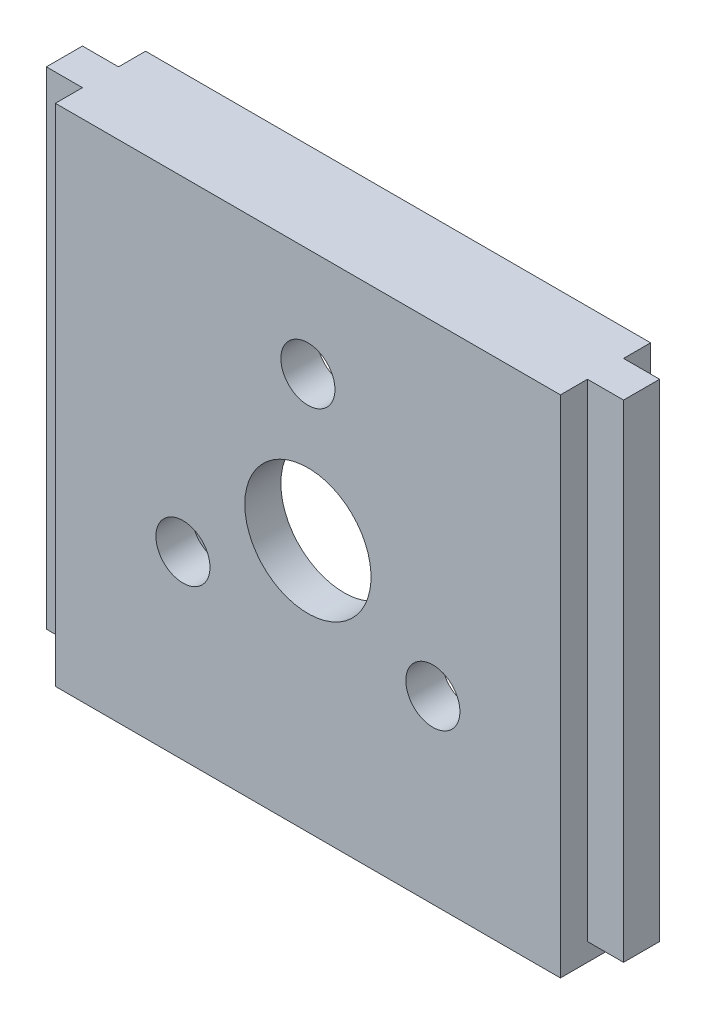
SolidWorks part; units mm, degrees
ref_plane "Plan de face" through (0, 0, 0) normal (0, 0, 1) x (1, 0, 0)
ref_plane "Plan de dessus" through (0, 0, 0) normal (0, 1, 0) x (1, 0, 0)
ref_plane "Plan de droite" through (0, 0, 0) normal (1, 0, 0) x (0, 0, -1)
sketch "Esquisse1" plane through (0, 0, 0) normal (0, 0, 1) x (1, 0, 0)
  line L1 (0, 0) -> (28, 0)
  line L2 (0, 0) -> (0, 28)
  line L3 (0, 28) -> (28, 28)
  line L4 (28, 0) -> (28, 28)
  dimension "D1" = 28
  dimension "D2" = 28
extrude "Boss.-Extru.1" add sketch "Esquisse1" along normal blind 5
sketch "Esquisse2" plane through (0, 0, 5) normal (0, 0, 1) x (1, 0, 0)
  line L0 (28, 28) -> (0, 0) construction
  circle A0 centre (14, 14) radius 3.5
  point P6 (10.5, 10.5)
  dimension "D1" = 7
extrude "Enlèv. mat.-Extru.1" cut sketch "Esquisse2" against normal through all and the other way through all
sketch "Esquisse3" plane through (0, 28, 0) normal (0, 1, 0) x (1, 0, 0)
  line L0 (0, -5) -> (0, 0) construction
  line L1 (0, -1.5) -> (-2, -1.5)
  line L2 (0, -1.5) -> (0, -3.5)
  line L3 (0, -3.5) -> (-2, -3.5)
  line L4 (-2, -1.5) -> (-2, -3.5)
  line L5 (28, -5) -> (0, -5) construction
  line L6 (14, 0) -> (14, -5) construction
  line L7 (28, 0) -> (0, 0) construction
  line L8 (28, -3.5) -> (30, -3.5)
  line L9 (30, -1.5) -> (30, -3.5)
  line L10 (28, -1.5) -> (30, -1.5)
  line L11 (28, -1.5) -> (28, -3.5)
  dimension "D1" = 2
  dimension "D2" = 2
  dimension "D3" = 1.5
extrude "Boss.-Extru.2" add sketch "Esquisse3" against normal blind 27
sketch "Esquisse5" plane through (0, 0, 0) normal (0, 0, -1) x (-1, 0, 0)
  line L0 (-14, 14) -> (-14, 22) construction
  line L1 (-14, 14) -> (-20.9282, 10) construction
  line L2 (-14, 14) -> (-7.0718, 10) construction
  circle A0 centre (-14, 22) radius 1.5
  circle A3 centre (-20.9282, 10) radius 1.5
  circle A4 centre (-7.0718, 10) radius 1.5
  dimension "D1" = 3
  dimension "D3" = 3
  dimension "D4" = 3
  dimension "D2" = 8
  dimension "D5" = 8
  dimension "D6" = 8
  dimension "D7" = 120
  dimension "D8" = 120
extrude "Enlèv. mat.-Extru.3" cut sketch "Esquisse5" against normal through all
sketch "Esquisse6" plane through (0, 0, 0) normal (0, 0, -1) x (-1, 0, 0)
  line L0 (0, 28) -> (-28, 0) construction
  circle A0 centre (-14, 14) radius 12.5
  point P6 (-13.5, 13.5)
  dimension "D1" = 25
extrude "Enlèv. mat.-Extru.4" cut sketch "Esquisse6" against normal blind 3
